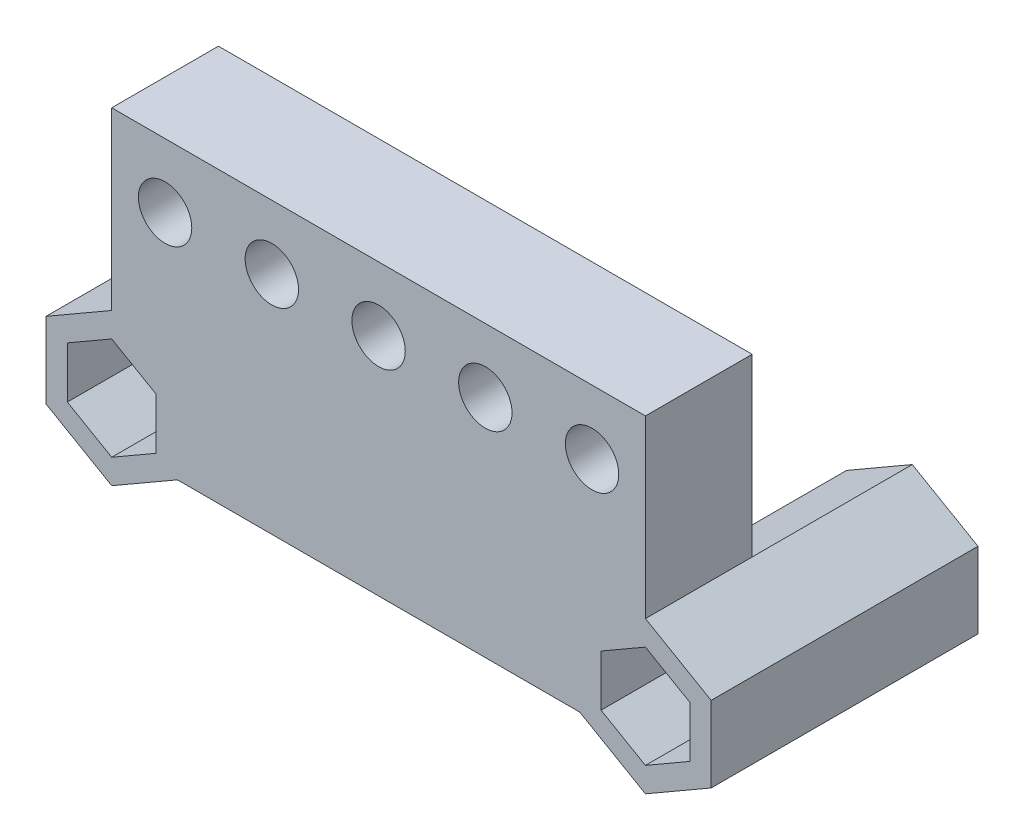
SolidWorks part; units mm, degrees
ref_plane "Front Plane" through (0, 0, 0) normal (0, 0, 1) x (1, 0, 0)
ref_plane "Top Plane" through (0, 0, 0) normal (0, 1, 0) x (1, 0, 0)
ref_plane "Right Plane" through (0, 0, 0) normal (1, 0, 0) x (0, 0, -1)
sketch "Sketch1" plane through (0, 0, 0) normal (0, 0, 1) x (1, 0, 0)
  line L0 (0, 0) -> (4.1569, 0) construction
  line L1 (-4.1569, 2.4) -> (-4.1569, -2.4)
  line L2 (-4.1569, -2.4) -> (0, -4.8)
  line L3 (0, -4.8) -> (4.1569, -2.4)
  line L4 (4.1569, -2.4) -> (4.1569, 2.4)
  line L5 (4.1569, 2.4) -> (0, 4.8)
  line L6 (0, 4.8) -> (-4.1569, 2.4)
  line L7 (45.8431, -2.4) -> (50, -4.8)
  line L8 (50, -4.8) -> (54.1569, -2.4)
  line L9 (54.1569, -2.4) -> (54.1569, 2.4)
  line L10 (54.1569, 2.4) -> (50, 4.8)
  line L11 (50, 4.8) -> (45.8431, 2.4)
  line L12 (45.8431, 2.4) -> (45.8431, -2.4)
  line L13 (50, 0) -> (45.8431, 0) construction
  line L14 (-6.1569, -3.5547) -> (0, -7.1094)
  line L15 (0, -7.1094) -> (6.1569, -3.5547)
  line L16 (6.1569, -3.5547) -> (6.1569, 3.5547)
  line L17 (6.1569, 3.5547) -> (0, 7.1094)
  line L18 (0, 7.1094) -> (-6.1569, 3.5547)
  line L19 (-6.1569, 3.5547) -> (-6.1569, -3.5547)
  line L20 (43.8431, -3.5547) -> (50, -7.1094)
  line L21 (50, -7.1094) -> (56.1569, -3.5547)
  line L22 (56.1569, -3.5547) -> (56.1569, 3.5547)
  line L23 (56.1569, 3.5547) -> (50, 7.1094)
  line L24 (50, 7.1094) -> (43.8431, 3.5547)
  line L25 (43.8431, 3.5547) -> (43.8431, -3.5547)
  circle A0 centre (0, 0) radius 4.1569 construction
  circle A1 centre (50, 0) radius 4.1569 construction
  dimension "D1" = 4.8
  dimension "D2" = 50
  dimension "D3" = 2
extrude "Boss-Extrude1" add sketch "Sketch1" along normal blind 25
sketch "Sketch2" plane through (6.1569, 0, 0) normal (1, 0, 0) x (0, 0, -1)
  line L0 (-25, 3.5547) -> (0, 3.5547) construction
  line L1 (-25, -3.5547) -> (-15, -3.5547)
  line L2 (-25, -3.5547) -> (-25, 3.5547)
  line L3 (-25, 3.5547) -> (-15, 3.5547)
  line L4 (-15, -3.5547) -> (-15, 3.5547)
  dimension "D1" = 10
extrude "Boss-Extrude2" add sketch "Sketch2" along normal up to surface (37.6862 mm away) up to face at (43.8431, 0, 12.5)
sketch "Sketch3" plane through (0, 0, 25) normal (0, 0, 1) x (1, 0, 0)
  line L0 (50, 7.1094) -> (50, 23.5547)
  line L1 (50, 23.5547) -> (0, 23.5547)
  line L2 (0, 23.5547) -> (0, 7.1094)
  line L3 (43.8431, 3.5547) -> (6.1569, 3.5547) construction
  line L4 (50, 7.1094) -> (43.8431, 3.5547)
  line L5 (43.8431, 3.5547) -> (6.1569, 3.5547)
  line L6 (6.1569, 3.5547) -> (0, 7.1094)
  dimension "D1" = 20
extrude "Boss-Extrude3" add sketch "Sketch3" against normal up to surface (10 mm away) up to face at (34.4215, -1.7774, 15)
sketch "Sketch4" plane through (0, 0, 25) normal (0, 0, 1) x (1, 0, 0)
  line L0 (0, 17.5547) -> (50, 17.5547) construction
  line L1 (0, 23.5547) -> (0, 7.1094) construction
  line L2 (50, 7.1094) -> (50, 23.5547) construction
  line L3 (25, 17.5547) -> (35, 17.5547) construction
  line L4 (25, 17.5547) -> (15, 17.5547) construction
  line L5 (50, 23.5547) -> (0, 23.5547) construction
  circle A0 centre (25, 17.5547) radius 2.5
  circle A1 centre (35, 17.5547) radius 2.5
  circle A2 centre (45, 17.5547) radius 2.5
  circle A3 centre (15, 17.5547) radius 2.5
  circle A4 centre (5, 17.5547) radius 2.5
  dimension "D1" = 5
  dimension "D4" = 3
  dimension "D5" = 10
  dimension "D6" = 6
  dimension "D3" = 10
  dimension "D2" = 3
extrude "Cut-Extrude1" cut sketch "Sketch4" against normal through all
